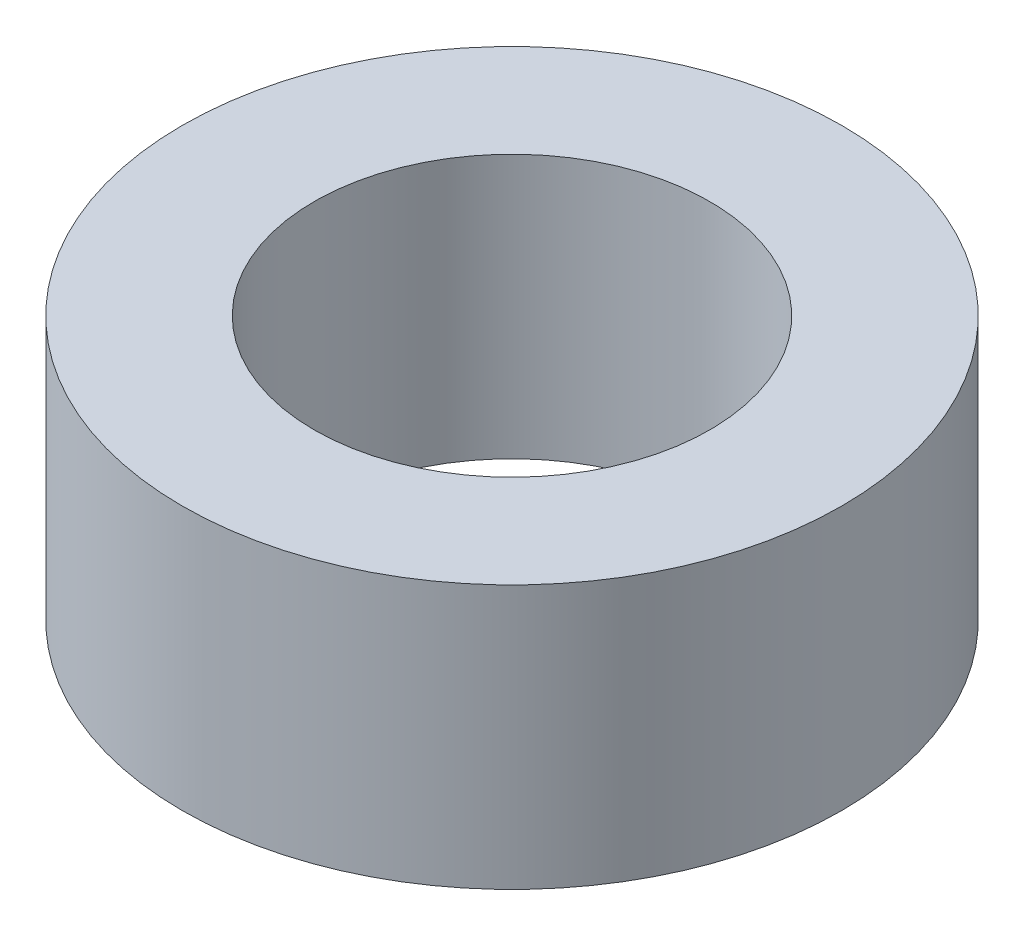
SolidWorks part; units mm, degrees
ref_plane "Front Plane" through (0, 0, 0) normal (0, 0, 1) x (1, 0, 0)
ref_plane "Top Plane" through (0, 0, 0) normal (0, 1, 0) x (1, 0, 0)
ref_plane "Right Plane" through (0, 0, 0) normal (1, 0, 0) x (0, 0, -1)
sketch "Sketch1" plane through (0, 0, 0) normal (0, 1, 0) x (1, 0, 0)
  circle A0 centre (0, 0) radius 15.875
  circle A1 centre (0, 0) radius 9.525
  dimension "D1" = 31.75
  dimension "D2" = 19.05
extrude "Boss-Extrude1" add sketch "Sketch1" along normal blind 12.7
